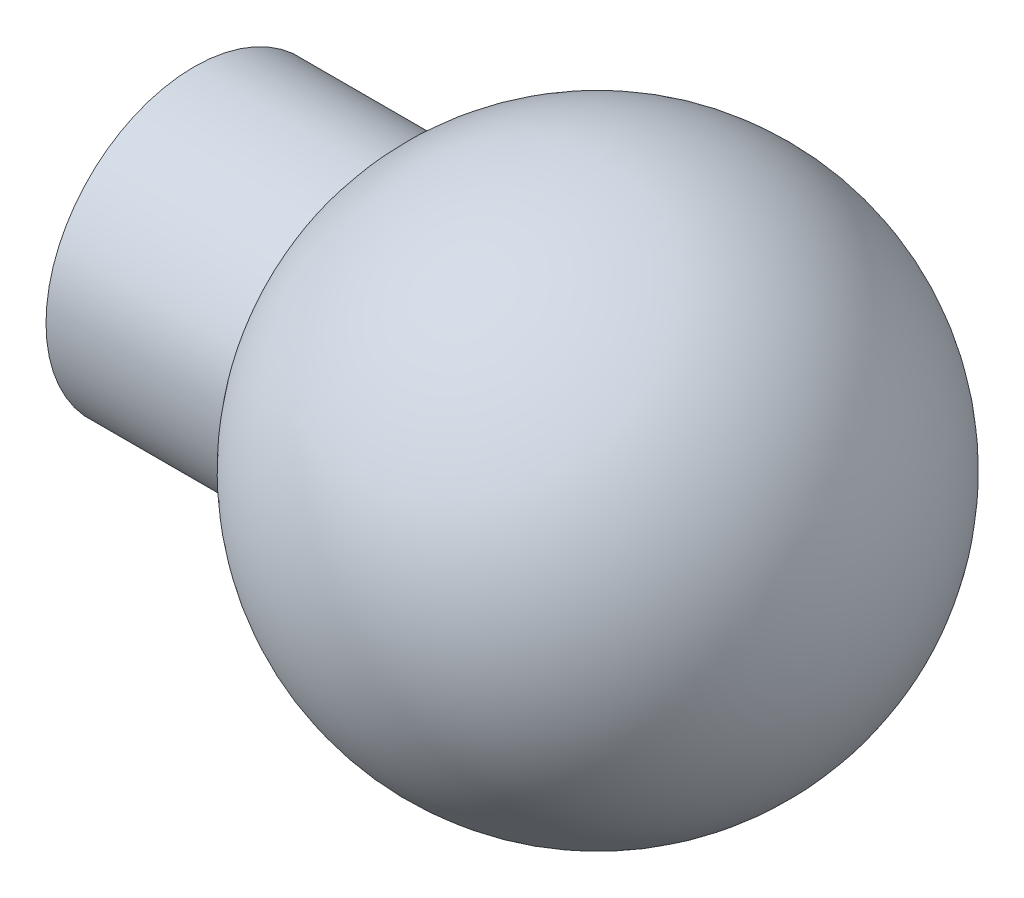
SolidWorks part; units mm, degrees
ref_plane "Front Plane" through (0, 0, 0) normal (0, 0, 1) x (1, 0, 0)
ref_plane "Top Plane" through (0, 0, 0) normal (0, 1, 0) x (1, 0, 0)
ref_plane "Right Plane" through (0, 0, 0) normal (1, 0, 0) x (0, 0, -1)
sketch "Sketch1" plane through (0, 0, 0) normal (0, 0, 1) x (1, 0, 0)
  line L0 (-20, 0) -> (20, 0) construction
  line L1 (20, 0) -> (-20, 0)
  arc A0 (20, 0) -> (-20, 0) centre (0, 0) ccw
  point P5 (0, 0)
revolve "Revolve1" add sketch "Sketch1" angle 360 about L0
sketch "Sketch2" plane through (0, 0, 0) normal (0, 0, 1) x (1, 0, 0)
  point P0 (0, 0)
sketch "Sketch3" plane through (0, 0, 0) normal (1, 0, 0) x (0, 0, -1)
  circle A0 centre (0, 0) radius 11
  dimension "D1" = 22
extrude "Boss-Extrude1" add sketch "Sketch3" against normal blind 30
sketch "Sketch4" plane through (-30, 0, 0) normal (-1, 0, 0) x (0, 0, 1)
  line L0 (0, -11) -> (0, 11) construction
  line L2 (-3.5, -3.5) -> (3.5, -3.5)
  line L3 (-3.5, -3.5) -> (-3.5, 3.5)
  line L4 (-3.5, 3.5) -> (3.5, 3.5)
  line L5 (3.5, -3.5) -> (3.5, 3.5)
  line L6 (-3.5, -3.5) -> (3.5, 3.5) construction
  line L7 (-3.5, 3.5) -> (3.5, -3.5) construction
  circle A0 centre (0, 0) radius 11 construction
  point P0 (0, 0)
  point P7 (0, 0)
  dimension "D1" = 7
  dimension "D2" = 7
extrude "Cut-Extrude1" cut sketch "Sketch4" against normal blind 6
